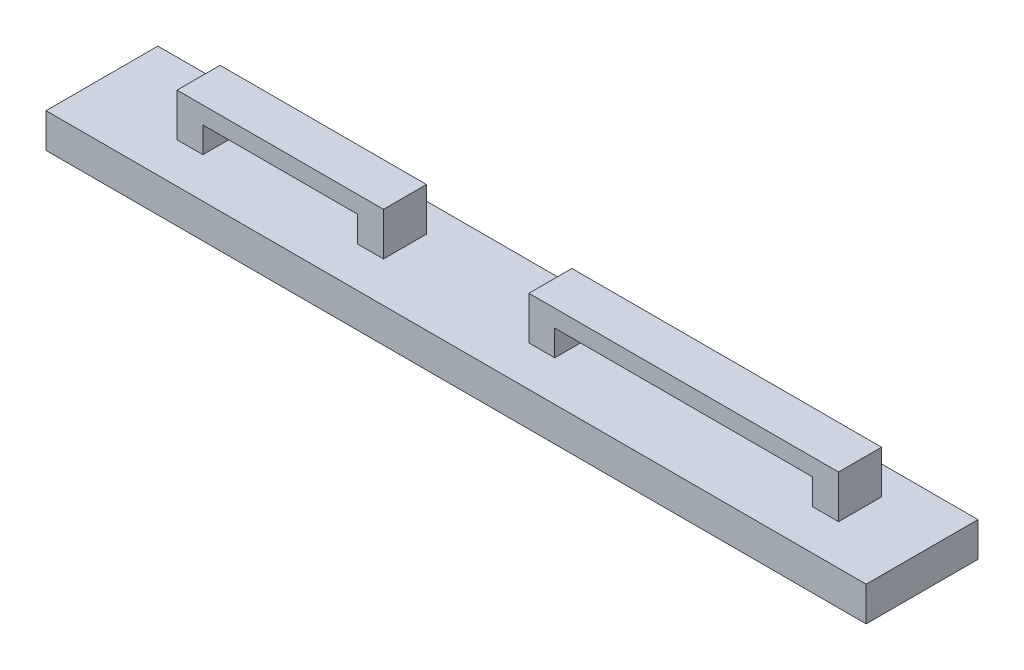
SolidWorks part; units mm, degrees
ref_plane "Front Plane" through (0, 0, 0) normal (0, 0, 1) x (1, 0, 0)
ref_plane "Top Plane" through (0, 0, 0) normal (0, 1, 0) x (1, 0, 0)
ref_plane "Right Plane" through (0, 0, 0) normal (1, 0, 0) x (0, 0, -1)
sketch "Sketch1" plane through (0, 0, 0) normal (0, 1, 0) x (1, 0, 0)
  line L1 (-23.8392, 6.5022) -> (23.8392, 6.5022)
  line L2 (-23.8392, 6.5022) -> (-23.8392, -6.5022)
  line L3 (-23.8392, -6.5022) -> (23.8392, -6.5022)
  line L4 (23.8392, 6.5022) -> (23.8392, -6.5022)
  line L5 (-23.8392, 6.5022) -> (23.8392, -6.5022) construction
  line L6 (-23.8392, -6.5022) -> (23.8392, 6.5022) construction
  point P0 (0, 0)
extrude "Boss-Extrude1" add sketch "Sketch1" along normal blind 2
sketch "Sketch2" plane through (0, 2, 0) normal (0, 1, 0) x (1, 0, 0)
  line L0 (-18.564, -1.6586) -> (-17.064, -1.6586)
  line L1 (-18.564, -1.6586) -> (-18.564, -4.1586)
  line L2 (-18.564, -4.1586) -> (-17.064, -4.1586)
  line L3 (-17.064, -1.6586) -> (-17.064, -4.1586)
  line L4 (-18.564, -1.6586) -> (-17.064, -4.1586) construction
  line L5 (-18.564, -4.1586) -> (-17.064, -1.6586) construction
  line L6 (-8.064, -1.6586) -> (-6.564, -1.6586)
  line L7 (-8.064, -1.6586) -> (-8.064, -4.1586)
  line L8 (-8.064, -4.1586) -> (-6.564, -4.1586)
  line L9 (-6.564, -1.6586) -> (-6.564, -4.1586)
  line L11 (1.891, -1.6586) -> (3.391, -1.6586)
  line L12 (1.891, -1.6586) -> (1.891, -4.1586)
  line L13 (1.891, -4.1586) -> (3.391, -4.1586)
  line L14 (3.391, -1.6586) -> (3.391, -4.1586)
  line L15 (18.391, -1.6586) -> (19.891, -1.6586)
  line L16 (18.391, -1.6586) -> (18.391, -4.1586)
  line L17 (18.391, -4.1586) -> (19.891, -4.1586)
  line L18 (19.891, -1.6586) -> (19.891, -4.1586)
  point P0 (-17.814, -2.9086)
  dimension "D1" = 2.5
  dimension "D2" = 1.5
  dimension "D3" = 1.5
  dimension "D4" = 9
  dimension "D5" = 1.5
  dimension "D6" = 2.5
  dimension "D7" = 15
  dimension "D8" = 1.5
  dimension "D9" = 2.5
extrude "Boss-Extrude2" add sketch "Sketch2" along normal blind 1.5
sketch "Sketch3" plane through (0, 3.5, 0) normal (0, 1, 0) x (1, 0, 0)
  line L1 (-18.564, -1.6586) -> (-6.564, -1.6586)
  line L2 (-18.564, -1.6586) -> (-18.564, -4.1586)
  line L3 (-18.564, -4.1586) -> (-6.564, -4.1586)
  line L4 (-6.564, -1.6586) -> (-6.564, -4.1586)
  line L5 (1.891, -1.6586) -> (19.891, -1.6586)
  line L6 (1.891, -1.6586) -> (1.891, -4.1586)
  line L7 (1.891, -4.1586) -> (19.891, -4.1586)
  line L8 (19.891, -1.6586) -> (19.891, -4.1586)
extrude "Boss-Extrude3" add sketch "Sketch3" along normal blind 1
sketch "Sketch4" plane through (0, 2, 0) normal (0, 1, 0) x (1, 0, 0)
  line L0 (23.8392, -6.5022) -> (23.8392, 6.5022) construction
  line L1 (-23.8392, 6.5022) -> (23.8392, 6.5022)
  line L2 (-23.8392, 6.5022) -> (-23.8392, 0)
  line L3 (-23.8392, 0) -> (23.8392, 0)
  line L4 (23.8392, 6.5022) -> (23.8392, 0)
extrude "Cut-Extrude1" cut sketch "Sketch4" against normal through all
